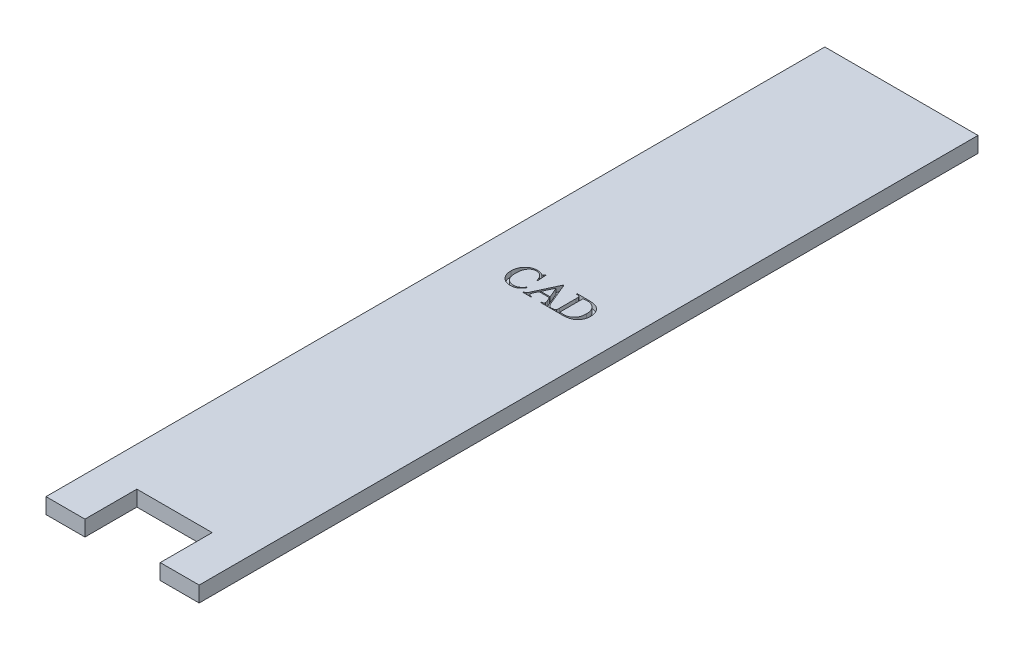
SolidWorks part; units mm, degrees
ref_plane "Front Plane" through (0, 0, 0) normal (0, 0, 1) x (1, 0, 0)
ref_plane "Top Plane" through (0, 0, 0) normal (0, 1, 0) x (1, 0, 0)
ref_plane "Right Plane" through (0, 0, 0) normal (1, 0, 0) x (0, 0, -1)
sketch "Sketch2" plane through (0, 0, 0) normal (0, 0, 1) x (1, 0, 0)
  line L1 (-14.75, 1.5) -> (14.75, 1.5)
  line L2 (-14.75, 1.5) -> (-14.75, -1.5)
  line L3 (-14.75, -1.5) -> (14.75, -1.5)
  line L4 (14.75, 1.5) -> (14.75, -1.5)
  line L5 (-14.75, 1.5) -> (14.75, -1.5) construction
  line L6 (-14.75, -1.5) -> (14.75, 1.5) construction
  point P0 (0, 0)
  dimension "D1" = 29.5
  dimension "D2" = 3
extrude "Boss-Extrude1" add sketch "Sketch2" along normal blind 150
sketch "Sketch4" plane through (0, 1.5, 0) normal (0, 1, 0) x (1, 0, 0)
  line L0 (14.75, -150) -> (-14.75, -150) construction
  line L1 (-7.25, -150) -> (7.25, -150)
  line L2 (-7.25, -150) -> (-7.25, -140)
  line L3 (-7.25, -140) -> (7.25, -140)
  line L4 (7.25, -150) -> (7.25, -140)
  line L5 (-7.25, -150) -> (7.25, -140) construction
  line L6 (-7.25, -140) -> (7.25, -150) construction
  line L7 (14.75, -150) -> (14.75, 0) construction
  line L8 (-14.75, -150) -> (-14.75, 0) construction
  point P4 (0, -145)
  dimension "D1" = 7.5
  dimension "D2" = 7.5
  dimension "D3" = 10
extrude "Cut-Extrude2" cut sketch "Sketch4" against normal through all
sketch "Sketch5" plane through (0, 1.5, 0) normal (0, 1, 0) x (1, 0, 0)
  line L0 (-14.75, -70) -> (14.75, -70) construction
  line L1 (-14.75, -150) -> (-14.75, 0) construction
  line L2 (14.75, -150) -> (14.75, 0) construction
  line L3 (-2.75, 0) -> (2.75, 0) construction
  text T0 "CAD" font "Times New Roman" height 5
  dimension "D1" = 70
extrude "Cut-Extrude3" cut sketch "Sketch5" against normal blind 1
